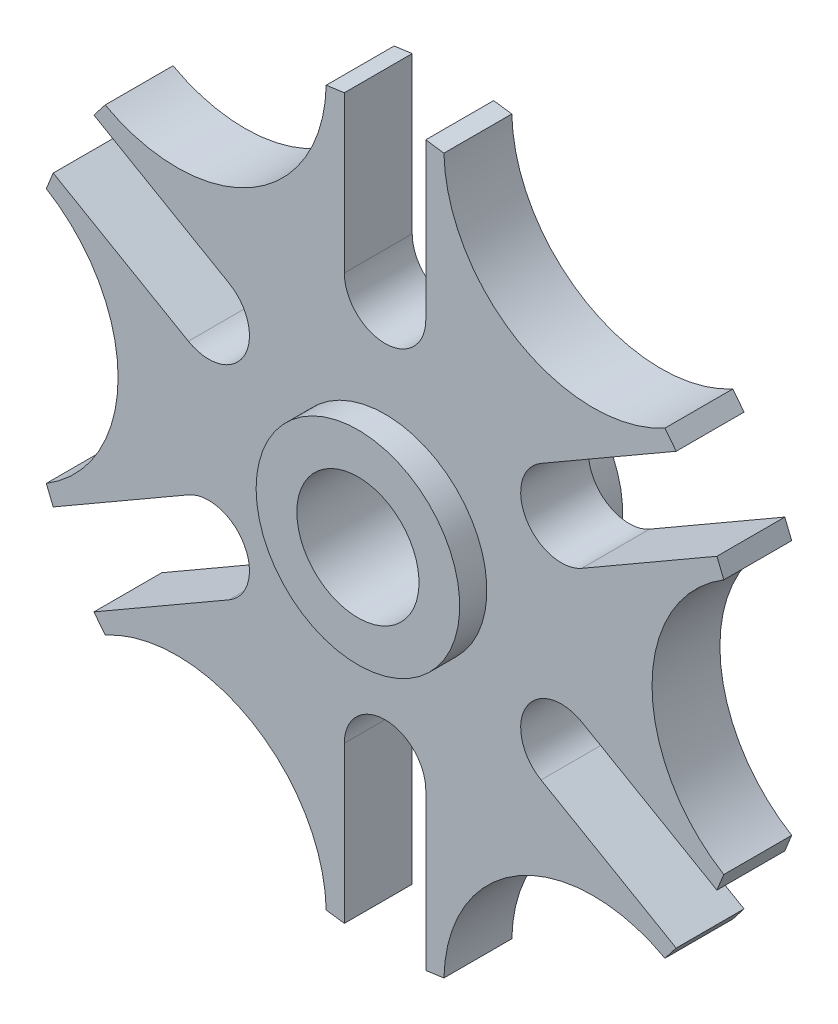
SolidWorks part; units mm, degrees
ref_plane "Piano frontale" through (0, 0, 0) normal (0, 0, 1) x (1, 0, 0)
ref_plane "Piano superiore" through (0, 0, 0) normal (0, 1, 0) x (1, 0, 0)
ref_plane "Piano destro" through (0, 0, 0) normal (1, 0, 0) x (0, 0, -1)
sketch "Schizzo6" plane through (0, 0, 0) normal (0, 1, 0) x (1, 0, 0)
  line L0 (0, 47.8944) -> (0, -19.8667) construction
  line L1 (13.5, 36) -> (22.5, 36)
  line L2 (22.5, 36) -> (22.5, 21)
  line L3 (22.5, 21) -> (80, 21)
  line L4 (80, 21) -> (80, 6)
  line L5 (80, 6) -> (22.5, 6)
  line L6 (22.5, 6) -> (22.5, 0)
  line L7 (22.5, 0) -> (13.5, 0)
  line L8 (13.5, 0) -> (13.5, 36)
  line L9 (0, 0) -> (57.5972, 0) construction
  point P5 (22.5, 3)
  dimension "D1" = 27
  dimension "D2" = 45
  dimension "D3" = 45
  dimension "D4" = 36
  dimension "D5" = 6
  dimension "D6" = 15
  dimension "D7" = 160
revolve "Rivoluzione1" add sketch "Schizzo6" angle 360 about L0
ref_plane "Piano1" through (22.5, 0, 0) normal (1, 0, 0) x (0, 0, -1)
hole_wizard "Foro Ø7.5 (7.5)-1" positions "Schizzo7" profile "Schizzo8" hole size "Ø7.5" standard "ISO" end condition through all
sketch "Schizzo7" plane through (22.5, 0, 0) normal (1, 0, 0) x (0, 0, -1)
  line L0 (0, 0) -> (46.9147, 0) construction
  line L2 (28.5, -22.5) -> (28.5, 22.5) construction
  line L3 (21, -22.5) -> (36, -22.5) construction
  line L4 (36, 22.5) -> (21, 22.5) construction
  line L6 (36, -22.5) -> (36, 22.5) construction
  point P14 (28.5, 0)
  dimension "D1" = 7.5
sketch "Schizzo8" plane through (22.5, 0, -28.5) normal (0, 1, 0) x (0, 0, -1)
  line L0 (0, 0) -> (0, 102.5)
  line L1 (0, 102.5) -> (3.75, 102.5)
  line L2 (3.75, 102.5) -> (3.75, 0)
  line L5 (3.75, 0) -> (0, 0)
  line L11 (0, -6.35) -> (0, 107.95) construction
  dimension "Thru Hole Dia." = 7.5
  dimension "Thru Hole Depth" = 102.5
sketch "Schizzo9" plane through (0, 0, -21) normal (0, 0, -1) x (-1, 0, 0)
  line L0 (0, 0) -> (0, 101.5947) construction
  line L1 (0, 80) -> (0, 45) construction
  line L4 (9, 79.4921) -> (9, 45)
  line L5 (-9, 79.4921) -> (-9, 45)
  line L6 (0, 0) -> (53.8349, 93.2447) construction
  line L7 (9, 79.4921) -> (13.0083, 78.9353)
  line L8 (64.3422, 47.5403) -> (34.4711, 30.2942)
  line L9 (73.3422, 31.9518) -> (43.4711, 14.7058)
  line L10 (73.3422, 31.9518) -> (74.8641, 28.2022)
  line L11 (73.3422, -31.9518) -> (43.4711, -14.7058)
  line L12 (64.3422, -47.5403) -> (34.4711, -30.2942)
  line L13 (64.3422, -47.5403) -> (61.8559, -50.7332)
  line L14 (9, -79.4921) -> (9, -45)
  line L15 (-9, -79.4921) -> (-9, -45)
  line L16 (-9, -79.4921) -> (-13.0083, -78.9353)
  line L17 (-64.3422, -47.5403) -> (-34.4711, -30.2942)
  line L18 (-73.3422, -31.9518) -> (-43.4711, -14.7058)
  line L19 (-73.3422, -31.9518) -> (-74.8641, -28.2022)
  line L20 (-73.3422, 31.9518) -> (-43.4711, 14.7058)
  line L21 (-64.3422, 47.5403) -> (-34.4711, 30.2942)
  line L22 (-64.3422, 47.5403) -> (-61.8559, 50.7332)
  line L23 (61.8559, 50.7332) -> (64.3422, 47.5403)
  line L24 (74.8641, -28.2022) -> (73.3422, -31.9518)
  line L25 (13.0083, -78.9353) -> (9, -79.4921)
  line L26 (-61.8559, -50.7332) -> (-64.3422, -47.5403)
  line L27 (-74.8641, 28.2022) -> (-73.3422, 31.9518)
  line L28 (-13.0083, 78.9353) -> (-9, 79.4921)
  arc A2 (34.4711, 30.2942) -> (43.4711, 14.7058) centre (38.9711, 22.5) ccw
  circle A3 centre (0, 0) radius 45 construction
  arc A5 (-9, 45) -> (9, 45) centre (0, 45) ccw
  arc A6 (74.8641, 28.2022) -> (74.8641, -28.2022) centre (92, 0) ccw
  circle A7 centre (0, 0) radius 80 construction
  circle A8 centre (0, 0) radius 92 construction
  arc A9 (13.0083, 78.9353) -> (61.8559, 50.7332) centre (46, 79.6743) ccw
  arc A10 (43.4711, -14.7058) -> (34.4711, -30.2942) centre (38.9711, -22.5) ccw
  arc A11 (61.8559, -50.7332) -> (13.0083, -78.9353) centre (46, -79.6743) ccw
  arc A12 (9, -45) -> (-9, -45) centre (0, -45) ccw
  arc A13 (-13.0083, -78.9353) -> (-61.8559, -50.7332) centre (-46, -79.6743) ccw
  arc A14 (-34.4711, -30.2942) -> (-43.4711, -14.7058) centre (-38.9711, -22.5) ccw
  arc A15 (-74.8641, -28.2022) -> (-74.8641, 28.2022) centre (-92, 0) ccw
  arc A16 (-43.4711, 14.7058) -> (-34.4711, 30.2942) centre (-38.9711, 22.5) ccw
  arc A17 (-61.8559, 50.7332) -> (-13.0083, 78.9353) centre (-46, 79.6743) ccw
  point P4 (0, 62.2461)
  point P62 (0, 0)
  dimension "D1" = 9
  dimension "D3" = 90
  dimension "D5" = 184
  dimension "D6" = 33
  dimension "D7" = 6
  dimension "D2" = 18
  dimension "D4" = 30
extrude "Taglio-Estrusione1" cut sketch "Schizzo9" against normal through all flip side to cut
sketch "Schizzo11" plane through (0, 0, 0) normal (0, 0, 1) x (1, 0, 0)
  line L0 (0, 0) -> (87.4896, 0)
